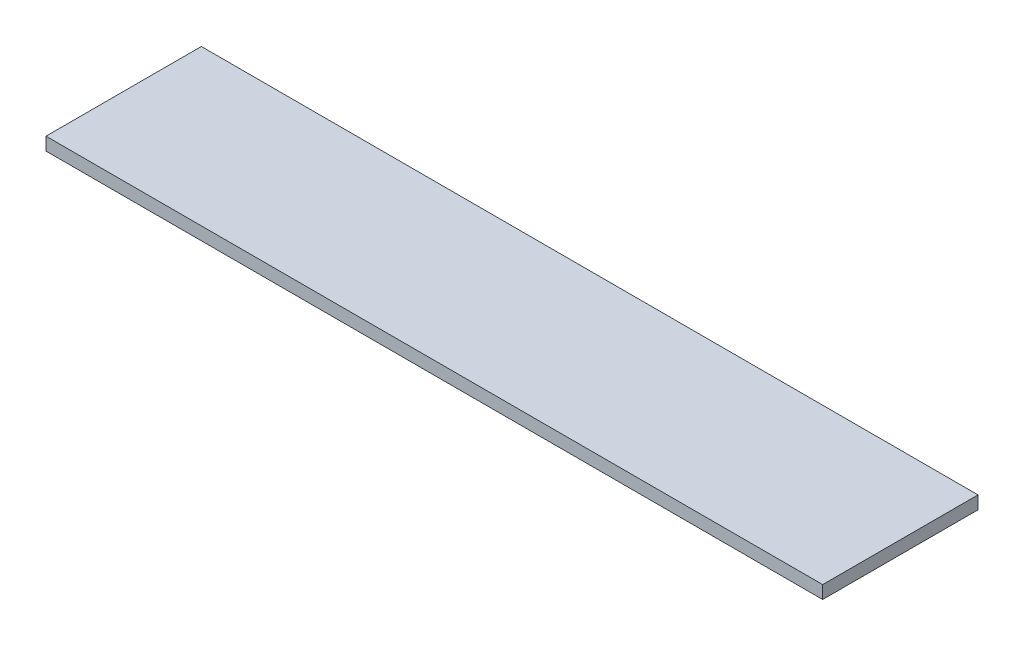
SolidWorks part; units mm, degrees
ref_plane "Front Plane" through (0, 0, 0) normal (0, 0, 1) x (1, 0, 0)
ref_plane "Top Plane" through (0, 0, 0) normal (0, 1, 0) x (1, 0, 0)
ref_plane "Right Plane" through (0, 0, 0) normal (1, 0, 0) x (0, 0, -1)
sketch "Sketch1" plane through (0, 0, 0) normal (0, 1, 0) x (1, 0, 0)
  line L1 (-190.5, -38.1) -> (190.5, -38.1)
  line L2 (-190.5, -38.1) -> (-190.5, 38.1)
  line L3 (-190.5, 38.1) -> (190.5, 38.1)
  line L4 (190.5, -38.1) -> (190.5, 38.1)
  line L5 (-190.5, -38.1) -> (190.5, 38.1) construction
  line L6 (-190.5, 38.1) -> (190.5, -38.1) construction
  point P0 (0, 0)
  dimension "D1" = 381
  dimension "D2" = 76.2
extrude "Boss-Extrude1" add sketch "Sketch1" along normal blind 6.35
